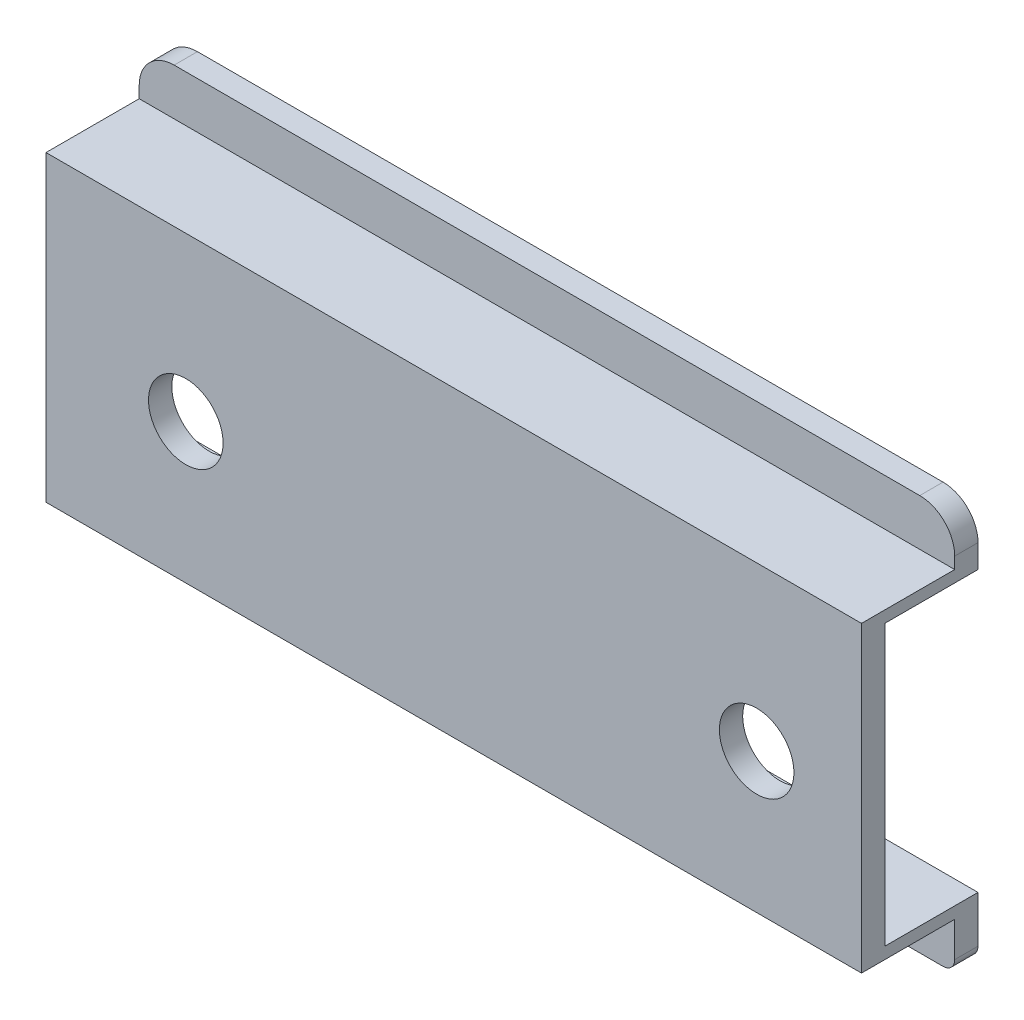
SolidWorks part; units mm, degrees
ref_plane "前视基准面" through (0, 0, 0) normal (0, 0, 1) x (1, 0, 0)
ref_plane "上视基准面" through (0, 0, 0) normal (0, 1, 0) x (1, 0, 0)
ref_plane "右视基准面" through (0, 0, 0) normal (1, 0, 0) x (0, 0, -1)
sketch "草图1" plane through (0, 0, 0) normal (0, 0, 1) x (1, 0, 0)
  line L0 (-163.8107, 118.6061) -> (186.1893, 118.6061)
  line L1 (186.1893, 118.6061) -> (186.1893, -51.3939)
  line L2 (186.1893, -51.3939) -> (-163.8107, -51.3939)
  line L3 (-163.8107, -51.3939) -> (-163.8107, 118.6061)
  line L4 (-163.8107, 33.6061) -> (288.8565, 33.6061) construction
  dimension "D1" = 350
  dimension "D2" = 170
extrude "凸台-拉伸1" add sketch "草图1" along normal blind 50
sketch "草图2" plane through (0, 0, 50) normal (0, 0, 1) x (1, 0, 0)
  line L0 (186.1893, -51.3939) -> (186.1893, 118.6061) construction
  line L1 (-163.8107, -51.3939) -> (186.1893, -51.3939)
  line L2 (-163.8107, -51.3939) -> (-163.8107, -31.3939)
  line L3 (-163.8107, -31.3939) -> (186.1893, -31.3939)
  line L4 (186.1893, -51.3939) -> (186.1893, -31.3939)
  line L6 (-163.8107, 118.6061) -> (186.1893, 118.6061)
  line L7 (-163.8107, 118.6061) -> (-163.8107, 98.6061)
  line L8 (-163.8107, 98.6061) -> (186.1893, 98.6061)
  line L9 (186.1893, 118.6061) -> (186.1893, 98.6061)
  dimension "D1" = 20
  dimension "D2" = 20
extrude "切除-拉伸1" cut sketch "草图2" against normal blind 40
sketch "草图3" plane through (0, 0, 0) normal (0, 0, -1) x (-1, 0, 0)
  line L0 (-186.1893, -51.3939) -> (-186.1893, 118.6061) construction
  line L1 (-186.1893, 93.6061) -> (163.8107, 93.6061)
  line L2 (-186.1893, 93.6061) -> (-186.1893, -26.3939)
  line L3 (-186.1893, -26.3939) -> (163.8107, -26.3939)
  line L4 (163.8107, 93.6061) -> (163.8107, -26.3939)
  line L5 (163.8107, 118.6061) -> (163.8107, -51.3939) construction
  dimension "D1" = 25
  dimension "D2" = 25
extrude "切除-拉伸2" cut sketch "草图3" against normal blind 40
sketch "草图4" plane through (0, 0, 50) normal (0, 0, 1) x (1, 0, 0)
  line L0 (-163.8107, -51.3939) -> (186.1893, -51.3939) construction
  line L2 (186.1893, -31.3939) -> (186.1893, 98.6061) construction
  line L3 (-163.8107, 98.6061) -> (-163.8107, -31.3939) construction
  circle A0 centre (-103.8107, 28.6061) radius 16
  circle A1 centre (141.1893, 28.6061) radius 16
  point P8 (186.1893, 38.6377)
  dimension "D1" = 32
  dimension "D2" = 32
  dimension "D3" = 80
  dimension "D4" = 80
  dimension "D5" = 45
  dimension "D6" = 60
extrude "切除-拉伸3" cut sketch "草图4" against normal through all contours A0 | A1
fillet "圆角1" radius 5 1 edges at (-163.8107, -51.3939, 5)
fillet "圆角2" radius 5 1 edges at (186.1893, -51.3939, 5)
fillet "圆角3" radius 15 1 edges at (186.1893, 118.6061, 5)
fillet "圆角4" radius 15 1 edges at (-163.8107, 118.6061, 5)
